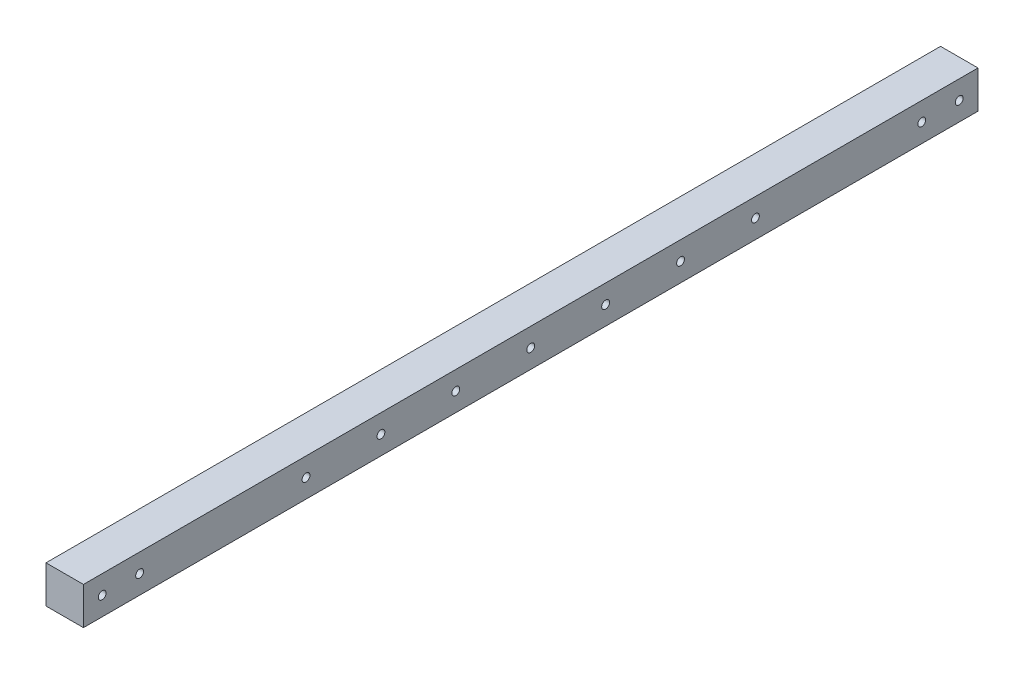
SolidWorks part; units mm, degrees
ref_plane "前视基准面" through (0, 0, 0) normal (0, 0, 1) x (1, 0, 0)
ref_plane "上视基准面" through (0, 0, 0) normal (0, 1, 0) x (1, 0, 0)
ref_plane "右视基准面" through (0, 0, 0) normal (1, 0, 0) x (0, 0, -1)
sketch "草图1" plane through (0, 0, 0) normal (0, 0, 1) x (1, 0, 0)
  line L1 (-10, 10) -> (10, 10)
  line L2 (-10, 10) -> (-10, -10)
  line L3 (-10, -10) -> (10, -10)
  line L4 (10, 10) -> (10, -10)
  line L5 (-10, 10) -> (10, -10) construction
  line L6 (-10, -10) -> (10, 10) construction
  point P0 (0, 0)
  dimension "D1" = 20
  dimension "D2" = 20
extrude "凸台-拉伸1" add sketch "草图1" along normal blind 477.69
sketch "草图2" plane through (10, 0, 0) normal (1, 0, 0) x (0, 0, -1)
  line L0 (-477.69, -10) -> (-477.69, 10) construction
  line L1 (-477.69, 10) -> (0, 10) construction
  line L2 (-238.845, 10) -> (-238.845, -10) construction
  line L3 (-477.69, -10) -> (0, -10) construction
  circle A0 centre (-467.69, 0) radius 2.1
  circle A1 centre (-447.69, 0) radius 2.1
  circle A2 centre (-10, 0) radius 2.1
  circle A3 centre (-30, 0) radius 2.1
  dimension "D1" = 4.2
  dimension "D2" = 4.2
  dimension "D3" = 10
  dimension "D4" = 20
  dimension "D5" = 10
  dimension "D6" = 10
extrude "切除-拉伸2" cut sketch "草图2" against normal through all
sketch "草图3" plane through (10, 0, 0) normal (1, 0, 0) x (0, 0, -1)
  line L0 (-238.845, 10) -> (-238.845, -10) construction
  line L1 (-477.69, 10) -> (0, 10) construction
  line L2 (-477.69, -10) -> (0, -10) construction
  circle A0 centre (-238.845, 0) radius 2.1
  circle A1 centre (-198.845, 0) radius 2.1
  circle A2 centre (-158.845, 0) radius 2.1
  circle A3 centre (-118.845, 0) radius 2.1
  circle A4 centre (-358.845, 0) radius 2.1
  circle A5 centre (-318.845, 0) radius 2.1
  circle A6 centre (-278.845, 0) radius 2.1
  dimension "D1" = 4.2
  dimension "D3" = 40
  dimension "D2" = 4
extrude "切除-拉伸3" cut sketch "草图3" against normal through all
